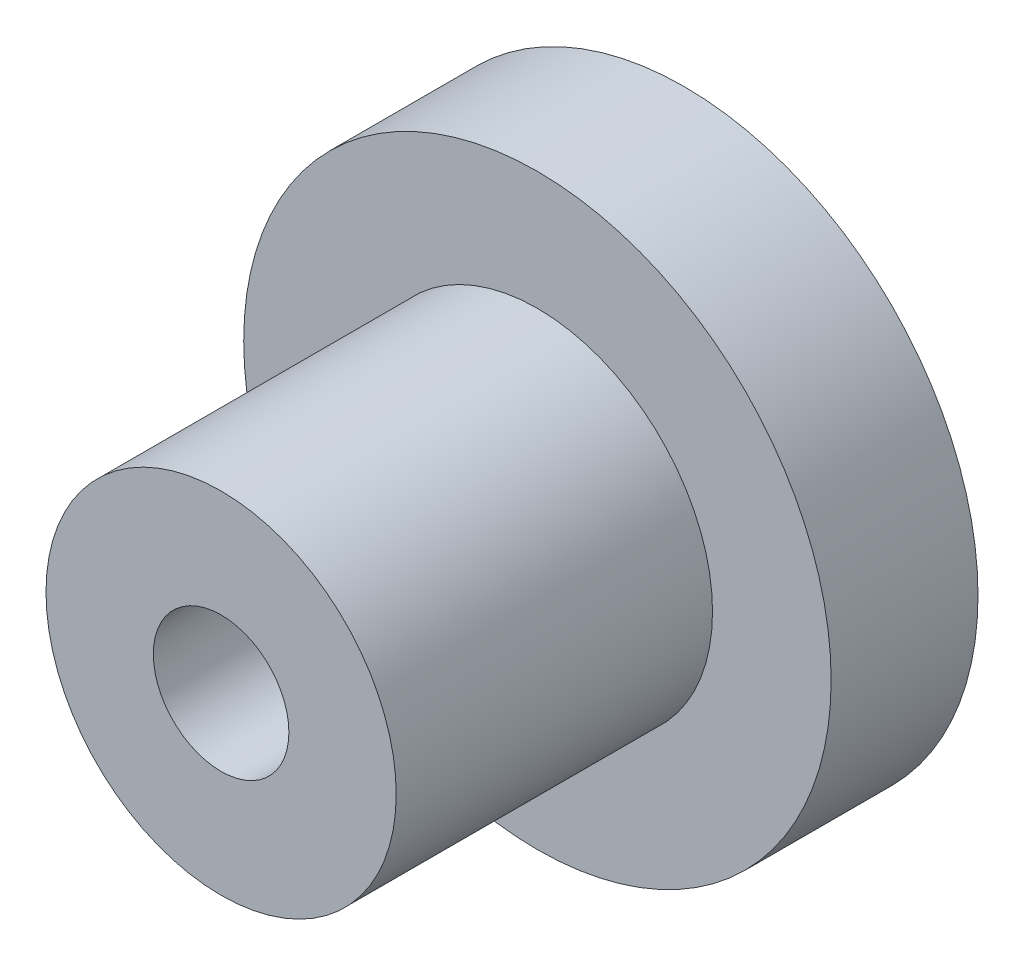
SolidWorks part; units mm, degrees
ref_plane "Front Plane" through (0, 0, 0) normal (0, 0, 1) x (1, 0, 0)
ref_plane "Top Plane" through (0, 0, 0) normal (0, 1, 0) x (1, 0, 0)
ref_plane "Right Plane" through (0, 0, 0) normal (1, 0, 0) x (0, 0, -1)
sketch "Sketch1" plane through (0, 0, 0) normal (0, 0, 1) x (1, 0, 0)
  circle A0 centre (0, 0) radius 1.5
  circle A1 centre (0, 0) radius 3.875
  dimension "D1" = 7.75
  dimension "D2" = 3
extrude "Boss-Extrude1" add sketch "Sketch1" along normal blind 7
sketch "Sketch2" plane through (0, 0, 0) normal (0, 0, -1) x (-1, 0, 0)
  circle A0 centre (0, 0) radius 1.5 construction
  circle A1 centre (0, 0) radius 1.5
  circle A2 centre (0, 0) radius 6.5
  dimension "D1" = 13
extrude "Boss-Extrude2" add sketch "Sketch2" along normal blind 3.25
